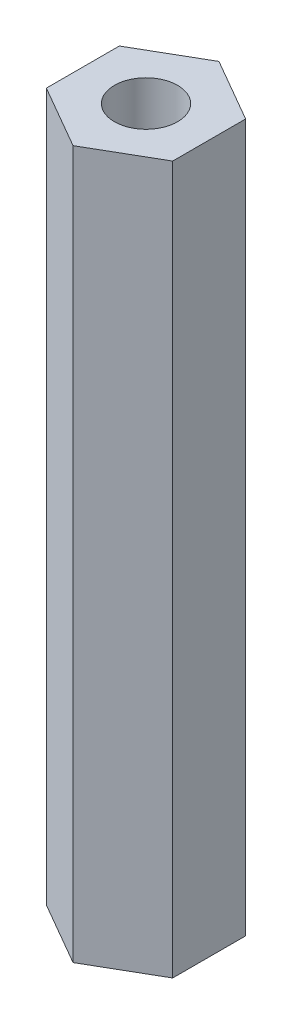
SolidWorks part; units mm, degrees
ref_plane "Front Plane" through (0, 0, 0) normal (0, 0, 1) x (1, 0, 0)
ref_plane "Top Plane" through (0, 0, 0) normal (0, 1, 0) x (1, 0, 0)
ref_plane "Right Plane" through (0, 0, 0) normal (1, 0, 0) x (0, 0, -1)
sketch "Sketch1" plane through (0, 0, 0) normal (0, 1, 0) x (1, 0, 0)
  line L1 (0, -7.3323) -> (6.35, -3.6662)
  line L2 (6.35, -3.6662) -> (6.35, 3.6662)
  line L3 (6.35, 3.6662) -> (0, 7.3323)
  line L4 (0, 7.3323) -> (-6.35, 3.6662)
  line L5 (-6.35, 3.6662) -> (-6.35, -3.6662)
  line L6 (-6.35, -3.6662) -> (0, -7.3323)
  circle A0 centre (0, 0) radius 6.35 construction
  dimension "D1" = 12.7
extrude "Boss-Extrude1" add sketch "Sketch1" along normal blind 71.12
sketch "Sketch2" plane through (0, 71.12, 0) normal (0, 1, 0) x (1, 0, 0)
  circle A0 centre (0, 0) radius 3.175
  dimension "D1" = 6.35
extrude "Cut-Extrude1" cut sketch "Sketch2" against normal through all both and the other way through all contours A0
